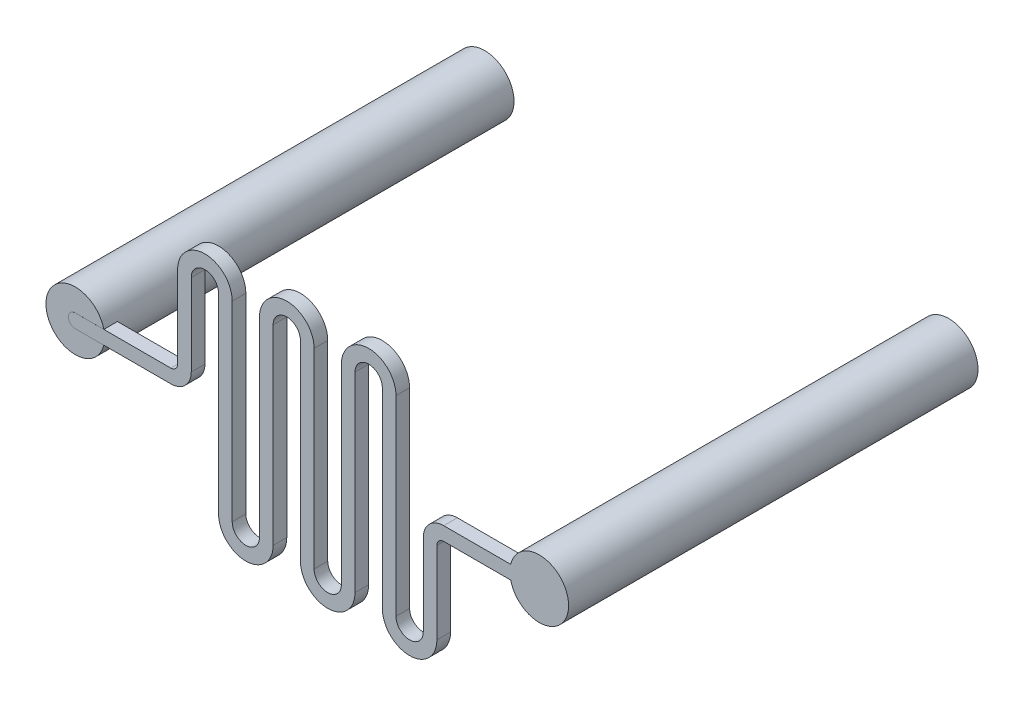
SolidWorks part; units mm, degrees
ref_plane "Front Plane" through (0, 0, 0) normal (0, 0, 1) x (1, 0, 0)
ref_plane "Top Plane" through (0, 0, 0) normal (0, 1, 0) x (1, 0, 0)
ref_plane "Right Plane" through (0, 0, 0) normal (1, 0, 0) x (0, 0, -1)
sketch "Sketch2" plane through (0, 0, 0) normal (0, 0, 1) x (1, 0, 0)
  line L3 (-20.5, -0.5) -> (-13.5, -0.5)
  line L6 (-12, 1) -> (-12, 7)
  line L9 (-10, 7) -> (-10, 0)
  line L12 (-10, 0) -> (-10, -7)
  line L15 (-6, -7) -> (-6, 0)
  line L18 (-6, 0) -> (-6, 7)
  line L21 (-4, 7) -> (-4, 0)
  line L22 (-4, 0) -> (-4, -7)
  line L23 (0, -7) -> (0, 0)
  line L24 (0, 0) -> (0, 7)
  line L25 (2, 7) -> (2, 0)
  line L26 (2, 0) -> (2, -7)
  line L27 (6, -7) -> (6, -1)
  line L28 (6.5, -0.5) -> (13.5, -0.5)
  line L29 (-20.5, 0.5) -> (-13.5, 0.5)
  line L30 (-13, 1) -> (-13, 7)
  line L31 (-9, 7) -> (-9, 0)
  line L32 (-9, 0) -> (-9, -7)
  line L33 (-7, -7) -> (-7, 0)
  line L34 (-7, 0) -> (-7, 7)
  line L35 (-3, 7) -> (-3, 0)
  line L36 (-3, 0) -> (-3, -7)
  line L37 (-1, -7) -> (-1, 0)
  line L38 (-1, 0) -> (-1, 7)
  line L39 (3, 7) -> (3, 0)
  line L40 (3, 0) -> (3, -7)
  line L41 (5, -7) -> (5, -1)
  line L42 (6.5, 0.5) -> (13.5, 0.5)
  arc A0 (-20.5, 0.5) -> (-20.5, -0.5) centre (-20.5, 0) ccw
  arc A1 (13.5, -0.5) -> (13.5, 0.5) centre (13.5, 0) ccw
  arc A8 (-12, 1) -> (-13.5, -0.5) centre (-13.5, 1) cw
  arc A9 (-12, 7) -> (-10, 7) centre (-11, 7) cw
  arc A10 (-10, -7) -> (-6, -7) centre (-8, -7) ccw
  arc A11 (-6, 7) -> (-4, 7) centre (-5, 7) cw
  arc A12 (-4, -7) -> (0, -7) centre (-2, -7) ccw
  arc A13 (0, 7) -> (2, 7) centre (1, 7) cw
  arc A14 (2, -7) -> (6, -7) centre (4, -7) ccw
  arc A15 (6, -1) -> (6.5, -0.5) centre (6.5, -1) cw
  arc A16 (-13, 1) -> (-13.5, 0.5) centre (-13.5, 1) cw
  arc A17 (-13, 7) -> (-9, 7) centre (-11, 7) cw
  arc A18 (-9, -7) -> (-7, -7) centre (-8, -7) ccw
  arc A19 (-7, 7) -> (-3, 7) centre (-5, 7) cw
  arc A20 (-3, -7) -> (-1, -7) centre (-2, -7) ccw
  arc A21 (-1, 7) -> (3, 7) centre (1, 7) cw
  arc A22 (3, -7) -> (5, -7) centre (4, -7) ccw
  arc A23 (5, -1) -> (6.5, 0.5) centre (6.5, -1) cw
  point P4 (0, 0)
  point P32 (5.5, 0)
  point P35 (-12.5, 0)
extrude "Boss-Extrude1" add sketch "Sketch2" along normal blind 1
ref_plane "Plane1" through (0, 0, 0) normal (0, 1, 0) x (1, 0, 0)
sketch "Sketch3" plane through (0, 0, 0) normal (0, 1, 0) x (1, 0, 0)
  line L0 (-20.5, -0.9984) -> (-22.65, -0.9984)
  line L1 (-20.5, -1) -> (-20.5, 0) construction
  line L3 (-20.5, -0.9984) -> (-20.5, 29.0016)
  line L4 (-20.5, 29.0016) -> (-22.65, 29.0016)
  line L5 (-22.65, 29.0016) -> (-22.65, -0.9984)
  dimension "D1" = 2.15
  dimension "D3" = 30
ref_plane "Plane2" through (0, 0, 0) normal (0, 1, 0) x (1, 0, 0)
sketch "Sketch4" plane through (0, 0, 0) normal (0, 1, 0) x (1, 0, 0)
  line L0 (13.5, -1) -> (15.65, -1)
  line L2 (13.5, -1) -> (13.5, 29)
  line L3 (13.5, 29) -> (15.65, 29)
  line L4 (15.65, 29) -> (15.65, -1)
  dimension "D3" = 30
  dimension "D4" = 2.15
revolve "Revolve1" add sketch "Sketch3" angle 360 about L3
revolve "Revolve2" add sketch "Sketch4" angle 360 about L2
sketch "Sketch5" plane through (0, 0, -29) normal (0, 0, -1) x (-1, 0, 0)
  circle A0 centre (-13.5, 0) radius 1.5
  circle A1 centre (20.5, 0) radius 1.5
  dimension "D1" = 3
  dimension "D2" = 3
extrude "Cut-Extrude1" cut sketch "Sketch5" against normal blind 28
sketch "Sketch6" plane through (0, 0, -29.0016) normal (0, 0, -1) x (-1, 0, 0)
  circle A0 centre (20.5, 0) radius 1.5
  dimension "D1" = 3
extrude "Cut-Extrude2" cut sketch "Sketch6" against normal blind 28
sketch "Sketch7" plane through (0, 0, 0.9984) normal (0, 0, 1) x (1, 0, 0)
  line L0 (-22.65, 0) -> (15.65, 0)
  arc A0 (-18.4089, 0.5) -> (-18.4089, -0.5) centre (-20.5, 0) ccw construction
  arc A1 (11.4089, -0.5) -> (11.4089, 0.5) centre (13.5, 0) ccw construction
